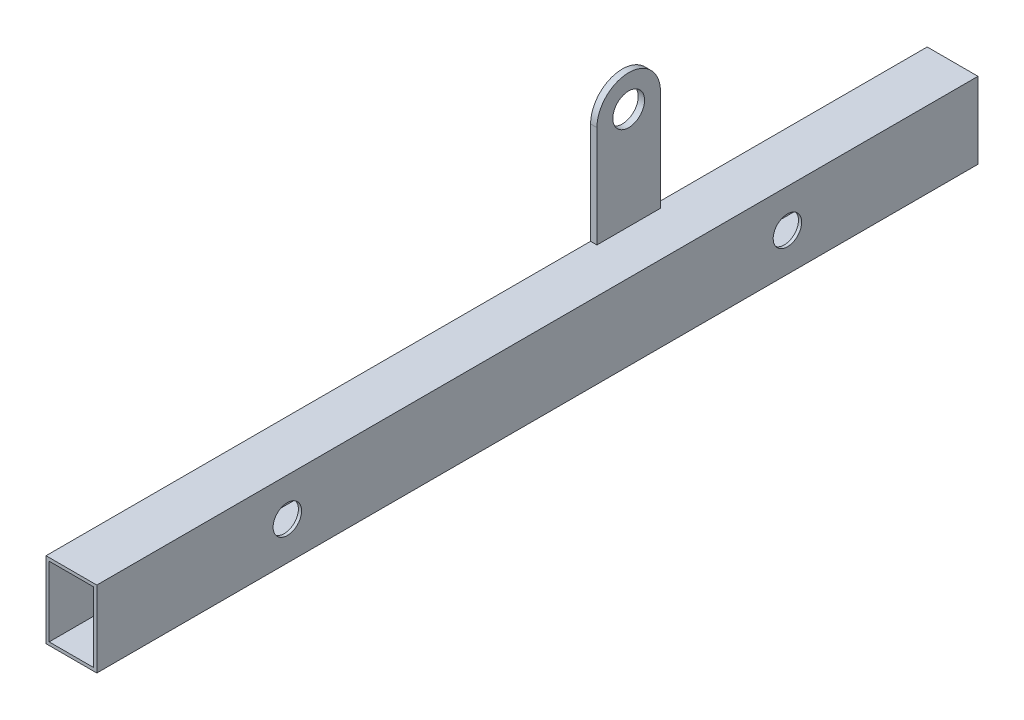
SolidWorks part; units mm, degrees
ref_plane "Front Plane" through (0, 0, 0) normal (0, 0, 1) x (1, 0, 0)
ref_plane "Top Plane" through (0, 0, 0) normal (0, 1, 0) x (1, 0, 0)
ref_plane "Right Plane" through (0, 0, 0) normal (1, 0, 0) x (0, 0, -1)
sketch "Sketch1" plane through (0, 0, 0) normal (0, 0, 1) x (1, 0, 0)
  line L0 (0, 38.1) -> (0, 34.925) construction
  line L1 (-25.4, 38.1) -> (25.4, 38.1)
  line L2 (-25.4, 38.1) -> (-25.4, -38.1)
  line L3 (-25.4, -38.1) -> (25.4, -38.1)
  line L4 (25.4, 38.1) -> (25.4, -38.1)
  line L5 (-25.4, 38.1) -> (25.4, -38.1) construction
  line L6 (-25.4, -38.1) -> (25.4, 38.1) construction
  line L7 (-22.225, 34.925) -> (22.225, 34.925)
  line L8 (-22.225, 34.925) -> (-22.225, -34.925)
  line L9 (-22.225, -34.925) -> (22.225, -34.925)
  line L10 (22.225, 34.925) -> (22.225, -34.925)
  line L11 (22.225, 0) -> (25.4, 0) construction
  line L12 (-22.225, 0) -> (-25.4, 0) construction
  line L13 (0, -34.925) -> (0, -38.1) construction
  point P0 (0, 0)
  dimension "D1" = 76.2
  dimension "D2" = 50.8
  dimension "D3" = 3.175
extrude "Boss-Extrude1" add sketch "Sketch1" along normal blind 965.2
sketch "Sketch2" plane through (0, 38.1, 0) normal (0, 1, 0) x (1, 0, 0)
  line L0 (-26.9875, -190.549) -> (26.9875, -190.549) construction
  line L1 (-25.4, 0) -> (25.4, 0)
  line L2 (-25.4, 0) -> (-25.4, -965.2)
  line L3 (-25.4, -965.2) -> (25.4, -965.2)
  line L4 (25.4, 0) -> (25.4, -965.2)
  line L5 (-26.4963, -703.2466) -> (26.4963, -703.2466) construction
  line L6 (0, -703.2466) -> (0, -190.549) construction
  line L7 (0, 0) -> (0, -190.549) construction
  line L8 (-74.6125, -402.6047) -> (-73.6301, -528.6965) construction
  line L9 (-74.1213, -465.6506) -> (-23.8125, -465.6506) construction
  line L10 (-23.8125, -465.6506) -> (26.9875, -465.6506) construction
  dimension "D1" = 190.549
  dimension "D2" = 512.6976
  dimension "D3" = 126.0917
  dimension "D4" = 50.3088
  dimension "D5" = 50.8
  dimension "D6" = 53.975
  dimension "D7" = 52.9926
  dimension "D8" = 275.1016
ref_plane "Plane1" through (25.4, 0, 0) normal (1, 0, 0) x (0, 0, -1)
sketch "Sketch4" plane through (25.4, 0, 0) normal (1, 0, 0) x (0, 0, -1)
  line L0 (-690.548, 38.1) -> (-690.548, 0) construction
  line L1 (-703.2466, 38.1) -> (-190.549, 38.1) construction
  line L2 (-190.549, 38.1) -> (-190.549, 0) construction
  line L3 (0, 38.1) -> (-190.549, 38.1) construction
  line L4 (-190.549, 0) -> (0, 0) construction
  line L5 (0, -38.1) -> (0, 38.1) construction
  line L6 (-190.549, 0) -> (-690.548, 0) construction
  circle A0 centre (-690.548, 0) radius 14.224
  circle A1 centre (-190.549, 0) radius 14.224
  dimension "D1" = 28.448
  dimension "D2" = 499.999
  dimension "D3" = 190.549
extrude "Cut-Extrude1" cut sketch "Sketch4" against normal up to surface (50.8 mm away) contours A1 | A0 up to face at (-25.4, 0, 482.6)
sketch "Sketch5" plane through (0, -38.1, 0) normal (0, -1, 0) x (1, 0, 0)
  line L0 (0, 0) -> (0, 283.21) construction
  line L1 (0, 283.21) -> (-25.4, 283.21) construction
  line L2 (-25.4, 965.2) -> (-25.4, 0) construction
  line L3 (-19.05, 283.21) -> (-19.05, 276.86) construction
  line L4 (-19.05, 283.21) -> (-19.05, 289.56) construction
  line L5 (-19.05, 289.56) -> (0, 289.56) construction
  line L6 (0, 289.56) -> (0, 410.718) construction
  line L7 (0, 410.718) -> (0, 580.898) construction
  circle A0 centre (-19.05, 276.86) radius 3.175
  circle A1 centre (-19.05, 289.56) radius 3.175
  circle A2 centre (19.05, 276.86) radius 3.175
  circle A3 centre (19.05, 289.56) radius 3.175
  circle A4 centre (0, 410.718) radius 3.175
  circle A5 centre (0, 580.898) radius 3.175
  circle A6 centre (0, 495.808) radius 3.175
  dimension "D5" = 6.35
  dimension "D8" = 6.35
  dimension "D1" = 283.21
  dimension "D2" = 6.35
  dimension "D3" = 6.35
  dimension "D4" = 6.35
  dimension "D6" = 121.158
  dimension "D7" = 170.18
extrude "Cut-Extrude2" cut sketch "Sketch5" against normal up to surface (3.175 mm away) up to face at (0, -34.925, 482.6)
sketch "Sketch6" plane through (25.4, 0, 0) normal (1, 0, 0) x (0, 0, -1)
  line L0 (0, 0) -> (-190.549, 0) construction
  line L1 (-690.548, 0) -> (-881.048, 0) construction
  line L2 (-881.048, 0) -> (-881.048, -38.1) construction
  line L3 (-965.2, -38.1) -> (0, -38.1) construction
  line L4 (-881.048, 0) -> (-881.048, 38.1) construction
  line L5 (-965.2, 38.1) -> (0, 38.1) construction
  line L7 (-881.048, 38.1) -> (-965.2, 38.1)
  line L8 (-881.048, 38.1) -> (-881.048, -38.1)
  line L9 (-881.048, -38.1) -> (-965.2, -38.1)
  line L10 (-965.2, 38.1) -> (-965.2, -38.1)
  dimension "D1" = 190.5
extrude "Cut-Extrude3" cut sketch "Sketch6" against normal up to surface (50.8 mm away) up to face at (-25.4, 14.224, 190.549)
sketch "Sketch7" plane through (-25.4, 0, 0) normal (-1, 0, 0) x (0, 0, 1)
  line L0 (336.55, 139.7) -> (336.55, 38.1)
  line L1 (881.048, 38.1) -> (0, 38.1) construction
  line L2 (336.55, 38.1) -> (273.05, 38.1)
  line L3 (273.05, 38.1) -> (273.05, 139.7)
  line L4 (0, 38.1) -> (0, -38.1) construction
  circle A0 centre (304.8, 139.7) radius 15.875
  arc A1 (336.55, 139.7) -> (273.05, 139.7) centre (304.8, 139.7) ccw
  point P10 (0, 0)
  dimension "D2" = 31.75
  dimension "D3" = 31.75
  dimension "D1" = 304.8
  dimension "D4" = 101.6
extrude "Boss-Extrude2" add sketch "Sketch7" against normal blind 6.35
